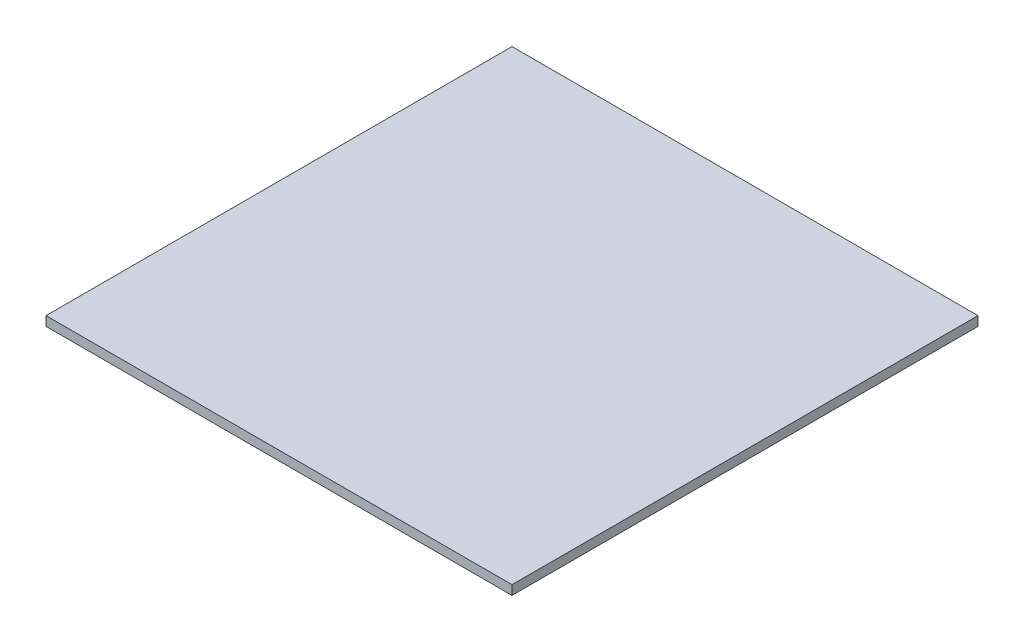
SolidWorks part; units mm, degrees
material "Teca"
ref_plane "Plano frontal" through (0, 0, 0) normal (0, 0, 1) x (1, 0, 0)
ref_plane "Plano superior" through (0, 0, 0) normal (0, 1, 0) x (1, 0, 0)
ref_plane "Plano direito" through (0, 0, 0) normal (1, 0, 0) x (0, 0, -1)
sketch "Esboço1" plane through (0, 0, 0) normal (0, 1, 0) x (1, 0, 0)
  line L1 (0, 0) -> (250, 0)
  line L2 (0, 0) -> (0, 250)
  line L3 (0, 250) -> (250, 250)
  line L4 (250, 0) -> (250, 250)
  dimension "D1" = 250
  dimension "D2" = 250
extrude "Ressalto-extrusão1" add sketch "Esboço1" against normal blind 5
